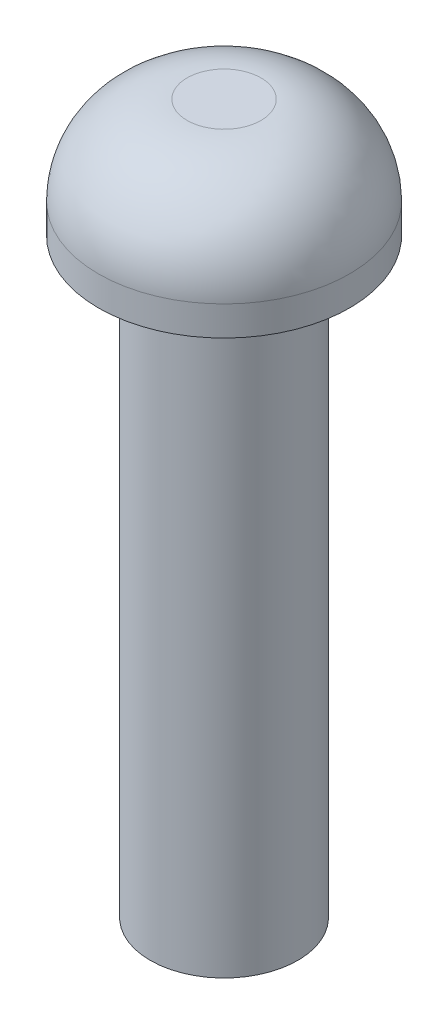
SolidWorks part; units mm, degrees
ref_plane "Alzado" through (0, 0, 0) normal (0, 0, 1) x (1, 0, 0)
ref_plane "Planta" through (0, 0, 0) normal (0, 1, 0) x (1, 0, 0)
ref_plane "Vista lateral" through (0, 0, 0) normal (1, 0, 0) x (0, 0, -1)
sketch "Croquis1" plane through (0, 0, 0) normal (0, 1, 0) x (1, 0, 0)
  circle A0 centre (0, 0) radius 2.5
  dimension "D1" = 5
extrude "Saliente-Extruir1" add sketch "Croquis1" along normal blind 20
sketch "Croquis2" plane through (0, 20, 0) normal (0, 1, 0) x (1, 0, 0)
  circle A0 centre (0, 0) radius 4.25
  dimension "D1" = 8.5
extrude "Saliente-Extruir2" add sketch "Croquis2" along normal blind 4
fillet "Redondeo1" radius 3 1 edges at (0, 24, 4.25)
